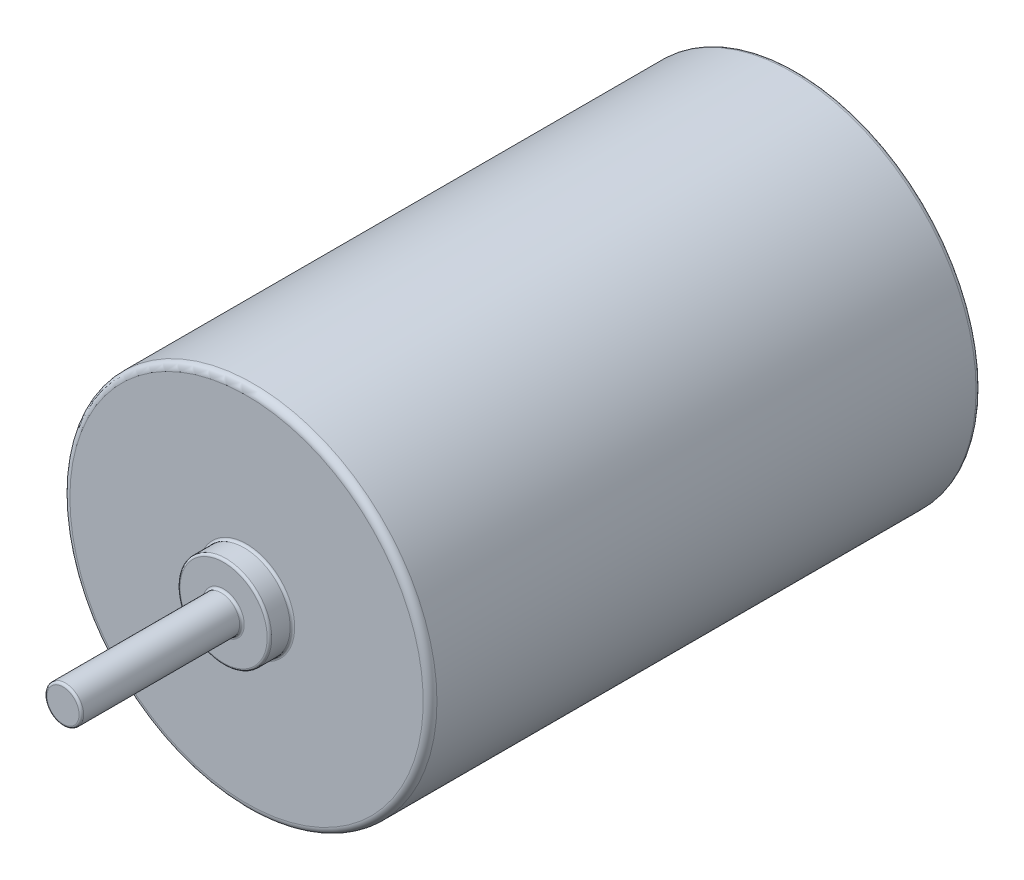
SolidWorks part; units mm, degrees
ref_plane "Front Plane" through (0, 0, 0) normal (0, 0, 1) x (1, 0, 0)
ref_plane "Top Plane" through (0, 0, 0) normal (0, 1, 0) x (1, 0, 0)
ref_plane "Right Plane" through (0, 0, 0) normal (1, 0, 0) x (0, 0, -1)
sketch "Sketch1" plane through (0, 0, 0) normal (1, 0, 0) x (0, 0, -1)
  line L0 (-94.8303, 0) -> (125.22, 0) construction
  line L1 (0, 4) -> (12, 4)
  line L2 (0, 55) -> (0, -55) construction
  line L3 (12, 4) -> (12, 0)
  line L4 (0, 4) -> (0, 1)
  line L5 (0, 1) -> (-0.5, 1)
  line L6 (-0.5, 1) -> (-0.5, 0.4)
  line L7 (-0.5, 0.4) -> (-4, 0.4)
  line L8 (-4, 0.4) -> (-4, 0)
  line L9 (12, 0) -> (-4, 0)
  dimension "D1" = 8
  dimension "D2" = 12
  dimension "D3" = 12.5
  dimension "D4" = 2
  dimension "D5" = 0.8
  dimension "D6" = 16
revolve "Revolve1" add sketch "Sketch1" angle 360 about L0
fillet "Fillet1" radius 0.05 4 edges at (0.4, 0, 4) (0.4, 0, 0.5) (1, 0, 0) (1, 0, 0.5)
fillet "Fillet3" radius 0.15 1 edges at (4, 0, 0)
fillet "Fillet4" radius 0.1 1 edges at (4, 0, -12)
